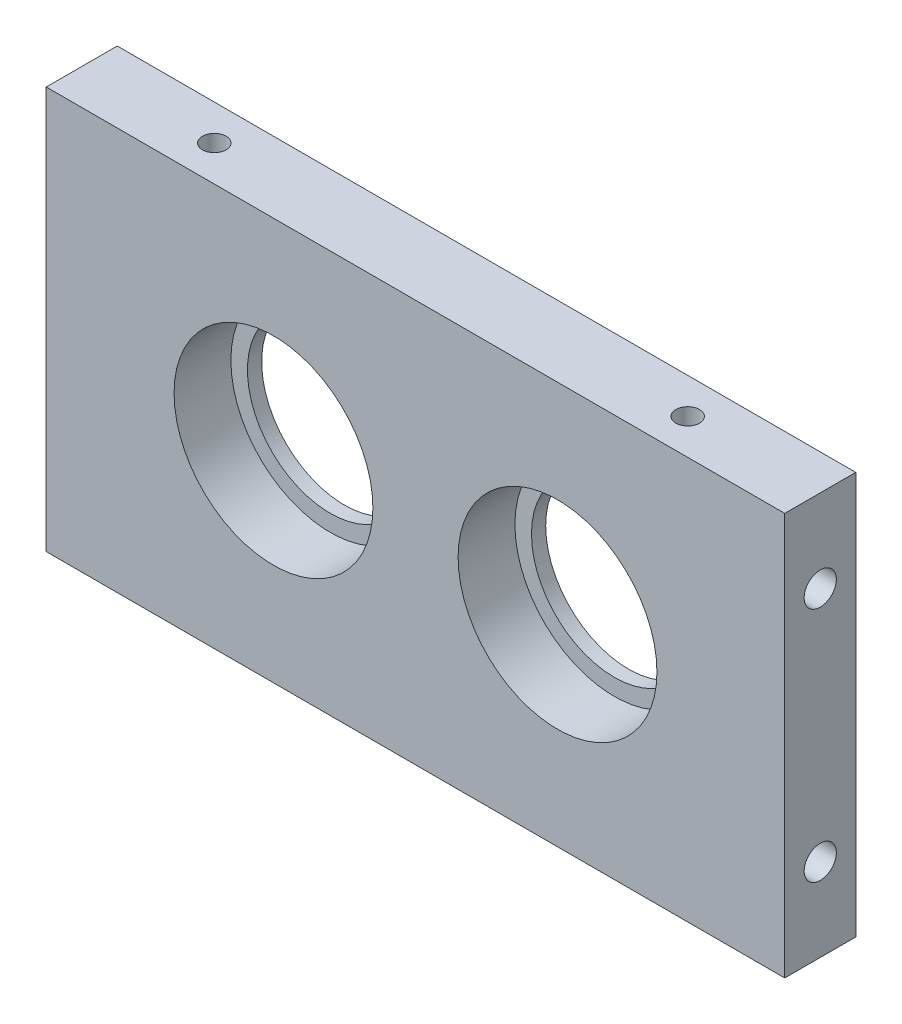
SolidWorks part; units mm, degrees
material "S45C"
ref_plane "Front Plane" through (0, 0, 0) normal (0, 0, 1) x (1, 0, 0)
ref_plane "Top Plane" through (0, 0, 0) normal (0, 1, 0) x (1, 0, 0)
ref_plane "Right Plane" through (0, 0, 0) normal (1, 0, 0) x (0, 0, -1)
sketch "Sketch1" plane through (0, 0, 0) normal (0, 0, 1) x (1, 0, 0)
  line L0 (0, 0) -> (0, 14.5427) construction
  line L1 (-78, -42.5) -> (78, -42.5)
  line L2 (-78, -42.5) -> (-78, 42.5)
  line L3 (-78, 42.5) -> (78, 42.5)
  line L4 (78, -42.5) -> (78, 42.5)
  line L5 (-78, -42.5) -> (78, 42.5) construction
  line L6 (-78, 42.5) -> (78, -42.5) construction
  circle A0 centre (-30, 0) radius 17.5
  circle A1 centre (30, 0) radius 17.5
  point P0 (0, 0)
  dimension "D3" = 35
  dimension "D4" = 60
  dimension "D1" = 85
  dimension "D2" = 156
extrude "Boss-Extrude1" add sketch "Sketch1" along normal mid plane 15
sketch "Sketch2" plane through (0, 0, 7.5) normal (0, 0, 1) x (1, 0, 0)
  circle A0 centre (-30, 0) radius 21
  circle A1 centre (30, 0) radius 21
  dimension "D1" = 42
extrude "Cut-Extrude1" cut sketch "Sketch2" against normal blind 12
sketch "Sketch3" plane through (-78, 0, 0) normal (-1, 0, 0) x (0, 0, 1)
  line L0 (0, 0) -> (18.9887, 0) construction
  circle A0 centre (0, 25) radius 2.5475
  circle A1 centre (0, -25) radius 2.5475
  dimension "D1" = 50
hole_wizard "M8 Tapped Hole1" positions "3DSketch1" profile "Sketch4" tap size "M8" standard "ISO"
sketch3d "3DSketch1"
  point P0 (-78, 25, 0)
  point P3 (-78, -25, 0)
  point P6 (78, 25, 0)
  point P8 (78, -25, 0)
sketch "Sketch4" plane through (-78, 25, 0) normal (0, 1, 0) x (0, 0, 1)
  line L0 (0, 0) -> (0, 21.7929)
  line L1 (0, 21.7929) -> (3.4, 19.75)
  line L2 (3.4, 19.75) -> (3.4, 0)
  line L5 (3.4, 0) -> (0, 0)
  line L10 (0, 21.7929) -> (-3.4, 19.75) construction
  line L11 (0, -6.35) -> (0, 107.95) construction
  dimension "Tap Drill Dia." = 6.8
  dimension "Tap Drill Depth" = 19.75
  dimension "Drill Angle" = 118
cosmetic thread "Hole Thread1" parameters "D1"=16, "D2"=8
cosmetic thread "Hole Thread2" parameters "D1"=16, "D2"=8
cosmetic thread "Hole Thread3" parameters "D1"=16, "D2"=8
cosmetic thread "Hole Thread4" parameters "D1"=16, "D2"=8
sketch "Sketch5" plane through (0, -42.5, 0) normal (0, -1, 0) x (1, 0, 0)
  line L0 (0, 0) -> (0, 13.7077) construction
  circle A0 centre (-50, 0) radius 2.0416
  circle A1 centre (50, 0) radius 2.0416
  dimension "D1" = 100
hole_wizard "M6 Tapped Hole1" positions "3DSketch2" profile "Sketch6" tap size "M6" standard "ISO"
sketch3d "3DSketch2"
  point P0 (-50, -42.5, 0)
  point P3 (50, -42.5, 0)
  point P6 (-50, 42.5, 0)
  point P8 (50, 42.5, 0)
sketch "Sketch6" plane through (-50, -42.5, 0) normal (1, 0, 0) x (0, 0, -1)
  line L0 (0, 0) -> (0, 16.5022)
  line L1 (0, 16.5022) -> (2.5, 15)
  line L2 (2.5, 15) -> (2.5, 0)
  line L5 (2.5, 0) -> (0, 0)
  line L10 (0, 16.5022) -> (-2.5, 15) construction
  line L11 (0, -6.35) -> (0, 107.95) construction
  dimension "Tap Drill Dia." = 5
  dimension "Tap Drill Depth" = 15
  dimension "Drill Angle" = 118
cosmetic thread "Hole Thread5" parameters "D1"=12, "D2"=6
cosmetic thread "Hole Thread6" parameters "D1"=12, "D2"=6
cosmetic thread "Hole Thread7" parameters "D1"=12, "D2"=6
cosmetic thread "Hole Thread8" parameters "D1"=12, "D2"=6
equation "\"Mass Kg\"= \"SW-Mass\""
